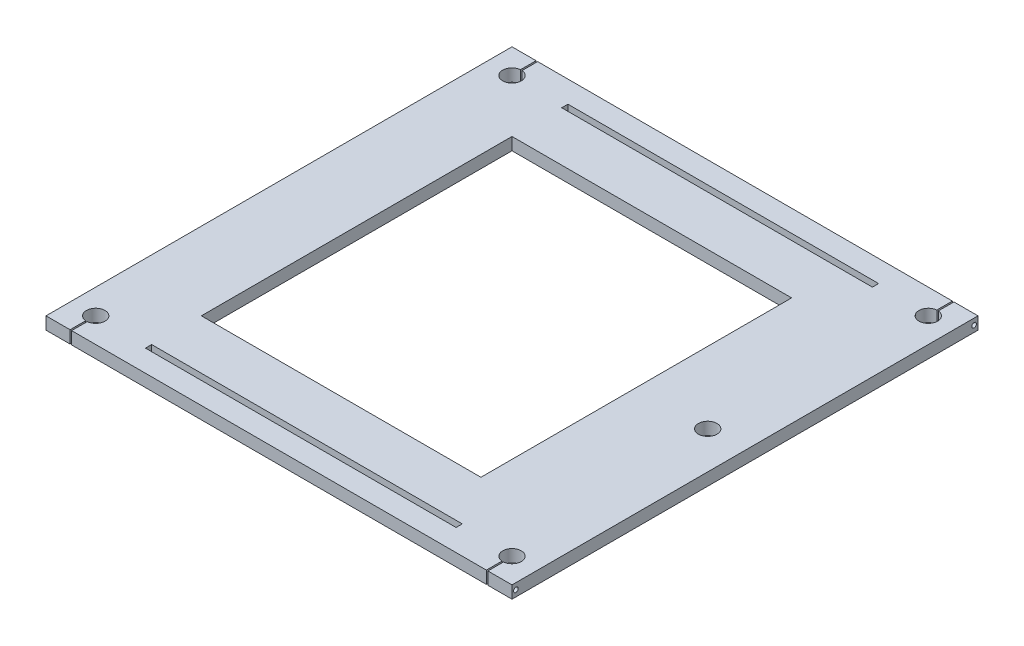
SolidWorks part; units mm, degrees
ref_plane "Front Plane" through (0, 0, 0) normal (0, 0, 1) x (1, 0, 0)
ref_plane "Top Plane" through (0, 0, 0) normal (0, 1, 0) x (1, 0, 0)
ref_plane "Right Plane" through (0, 0, 0) normal (1, 0, 0) x (0, 0, -1)
sketch "Sketch1" plane through (0, 0, 0) normal (0, 1, 0) x (1, 0, 0)
  line L0 (150, 150) -> (150, -150)
  line L1 (-150, -150) -> (150, -150)
  line L2 (-150, -150) -> (-150, 150)
  line L3 (-150, 150) -> (150, 150)
  line L4 (-10, 100) -> (-10, 150) construction
  line L5 (-150, -150) -> (150, 150) construction
  line L6 (-150, 150) -> (150, -150) construction
  line L7 (-100, -100) -> (80, -100)
  line L8 (-100, -100) -> (-100, 100)
  line L9 (-100, 100) -> (80, 100)
  line L10 (80, -100) -> (80, 100)
  line L11 (-100, -100) -> (80, 100) construction
  line L12 (-100, 100) -> (80, -100) construction
  line L14 (-100, 0) -> (-150, 0) construction
  line L15 (-10, -100) -> (-10, -150) construction
  point P0 (-10, 0)
  point P13 (0, 0)
  dimension "D4" = 300
  dimension "D1" = 300
  dimension "D2" = 180
  dimension "D3" = 200
extrude "Boss-Extrude1" add sketch "Sketch1" along normal blind 8
sketch "Sketch2" plane through (0, 0, 0) normal (0, 1, 0) x (1, 0, 0)
  line L0 (150, 150) -> (-150, 150) construction
  line L1 (150, 150) -> (-150, 150) construction
  line L2 (150, -150) -> (150, 150) construction
  line L3 (133.5, 150) -> (134.5, 150)
  line L4 (133.5, 150) -> (133.5, 139.9791)
  line L5 (134, 134) -> (134, 150) construction
  line L6 (134.5, 150) -> (134.5, 139.9791)
  arc A0 (133.5, 139.9791) -> (134.5, 139.9791) centre (134, 134) ccw
  point P6 (131.0158, 128.7948)
  dimension "D1" = 12
  dimension "D2" = 16
  dimension "D3" = 16
  dimension "D4" = 1
extrude "Cut-Extrude1" cut sketch "Sketch2" along normal through all
sketch "Sketch3" plane through (150, 0, 0) normal (1, 0, 0) x (0, 0, -1)
  line L0 (147.5, 4) -> (150, 4) construction
  line L2 (150, 8) -> (150, 0) construction
  circle A0 centre (147.5, 4) radius 1.5
  dimension "D1" = 3
  dimension "D2" = 2.5
extrude "Cut-Extrude2" cut sketch "Sketch3" against normal up to surface (16.5 mm away) up to face at (133.5, 4, -144.9896)
mirror "Mirror3" about plane through (0, 0, 0) normal (0, 0, 1) of "Cut-Extrude2", "Cut-Extrude1"
sketch "Sketch4" plane through (0, 0, 0) normal (0, 1, 0) x (1, 0, 0)
  line L3 (134, -866) -> (134, 49134) construction
  circle A0 centre (126, 0) radius 6
  dimension "D1" = 12
  dimension "D2" = 8
extrude "Cut-Extrude4" cut sketch "Sketch4" along normal through all
mirror "Mirror4" about plane through (0, 0, 0) normal (1, 0, 0) of "Cut-Extrude2", "Cut-Extrude1", "Mirror3"
sketch "Sketch5" plane through (0, 0, 0) normal (0, 1, 0) x (1, 0, 0)
  line L0 (-1134, 134) -> (48866, 134) construction
  line L2 (-100, 136) -> (100, 136)
  line L3 (-100, 136) -> (-100, 132)
  line L4 (-100, 132) -> (100, 132)
  line L5 (100, 136) -> (100, 132)
  line L6 (-100, 136) -> (100, 132) construction
  line L7 (-100, 132) -> (100, 136) construction
  point P1 (0, 134)
  dimension "D1" = 4
  dimension "D2" = 200
extrude "Cut-Extrude5" cut sketch "Sketch5" along normal through all
mirror "Mirror5" about plane through (0, 0, 0) normal (0, 0, 1) of "Cut-Extrude5"
